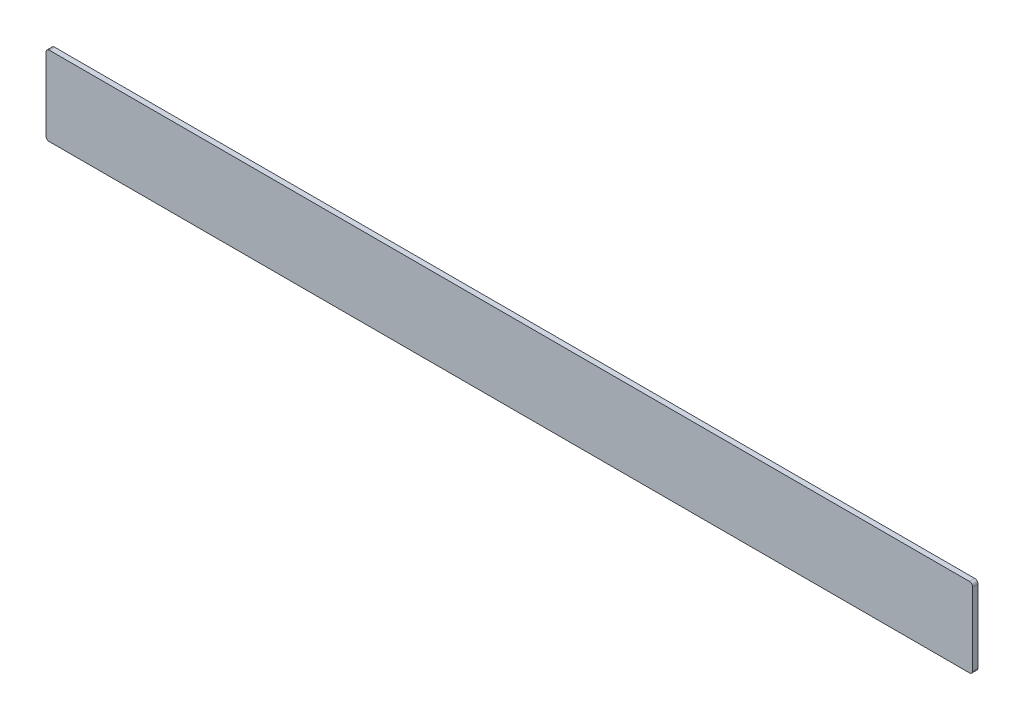
SolidWorks part; units mm, degrees
material "Plain Carbon Steel"
ref_plane "Front Plane" through (0, 0, 0) normal (0, 0, 1) x (1, 0, 0)
ref_plane "Top Plane" through (0, 0, 0) normal (0, 1, 0) x (1, 0, 0)
ref_plane "Right Plane" through (0, 0, 0) normal (1, 0, 0) x (0, 0, -1)
sketch "Sketch1" plane through (0, 0, 0) normal (0, 0, 1) x (1, 0, 0)
  line L1 (-697, -60) -> (697, -60)
  line L2 (-702, -55) -> (-702, 55)
  line L3 (-697, 60) -> (697, 60)
  line L4 (702, -55) -> (702, 55)
  line L5 (-702, -60) -> (702, 60) construction
  line L6 (-702, 60) -> (702, -60) construction
  line L7 (-702, 55) -> (-702, -55) construction
  arc A0 (702, -55) -> (697, -60) centre (697, -55) cw
  arc A1 (702, 55) -> (697, 60) centre (697, 55) ccw
  arc A2 (-697, -60) -> (-702, -55) centre (-697, -55) cw
  arc A3 (-702, 55) -> (-697, 60) centre (-697, 55) cw
  point P0 (0, 0)
  dimension "D1" = 5
  dimension "D2" = 120
extrude "Boss-Extrude1" add sketch "Sketch1" along normal mid plane 8
